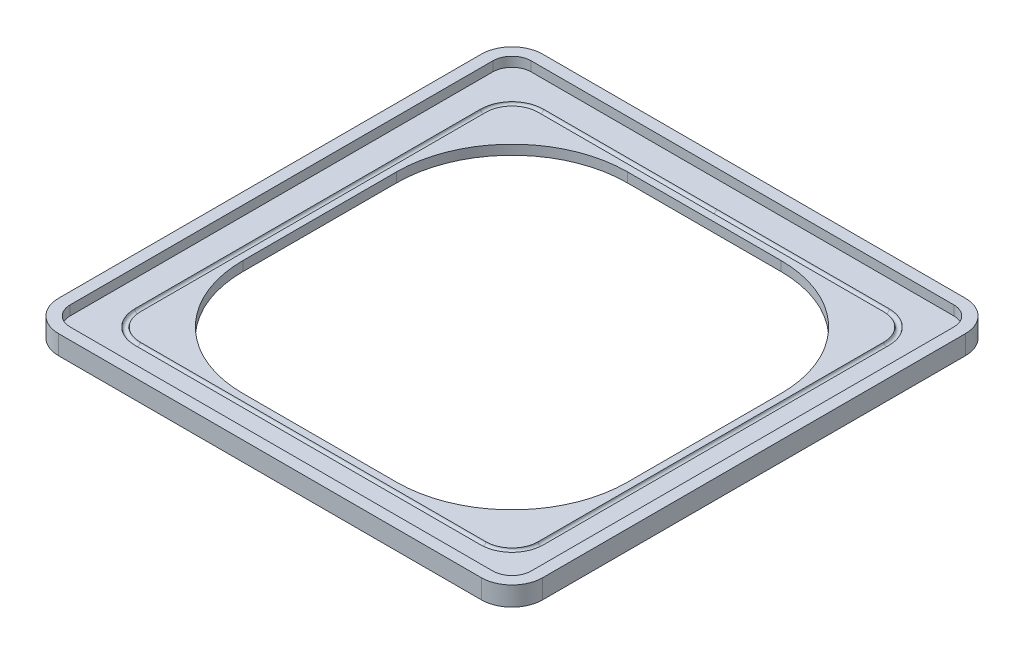
SolidWorks part; units mm, degrees
ref_plane "Front Plane" through (0, 0, 0) normal (0, 0, 1) x (1, 0, 0)
ref_plane "Top Plane" through (0, 0, 0) normal (0, 1, 0) x (1, 0, 0)
ref_plane "Right Plane" through (0, 0, 0) normal (1, 0, 0) x (0, 0, -1)
sketch "Sketch1" plane through (0, 0, 0) normal (0, 1, 0) x (1, 0, 0)
  line L0 (-127, 127) -> (127, 127)
  line L1 (-152.4, -152.4) -> (152.4, -152.4)
  line L2 (-152.4, -152.4) -> (-152.4, 152.4)
  line L3 (-152.4, 152.4) -> (152.4, 152.4)
  line L4 (152.4, -152.4) -> (152.4, 152.4)
  line L5 (-152.4, -152.4) -> (152.4, 152.4) construction
  line L6 (-152.4, 152.4) -> (152.4, -152.4) construction
  line L7 (127, -127) -> (127, 127)
  line L8 (-127, -127) -> (127, -127)
  line L9 (-127, -127) -> (-127, 127)
  line L10 (-146.05, -146.05) -> (-146.05, 146.05) construction
  line L11 (-146.05, 146.05) -> (146.05, 146.05) construction
  line L12 (146.05, -146.05) -> (146.05, 146.05) construction
  line L13 (-146.05, -146.05) -> (146.05, -146.05) construction
  point P0 (0, 0)
  dimension "D1" = 304.8
  dimension "D2" = 304.8
  dimension "D3" = 25.4
  dimension "D4" = 6.35
extrude "Boss-Extrude1" add sketch "Sketch1" along normal blind 6.35
fillet "Fillet1" radius 76.2 4 edges at (127, 3.175, 127) (-127, 3.175, 127) (-127, 3.175, -127) (127, 3.175, -127)
fillet "Fillet2" radius 12.7 4 edges at (-152.4, 3.175, 152.4) (-152.4, 3.175, -152.4) (152.4, 3.175, -152.4) (152.4, 3.175, 152.4)
sketch "Sketch3" plane through (0, 6.35, 0) normal (0, 1, 0) x (1, 0, 0)
  line L1 (114.3, -133.35) -> (-114.3, -133.35)
  line L2 (133.35, -114.3) -> (133.35, 114.3)
  line L3 (114.3, 133.35) -> (-114.3, 133.35)
  line L4 (-133.35, -114.3) -> (-133.35, 114.3)
  arc A0 (133.35, 114.3) -> (114.3, 133.35) centre (114.3, 114.3) ccw
  arc A1 (133.35, -114.3) -> (114.3, -133.35) centre (114.3, -114.3) cw
  arc A2 (-114.3, -133.35) -> (-133.35, -114.3) centre (-114.3, -114.3) cw
  arc A3 (-114.3, 133.35) -> (-133.35, 114.3) centre (-114.3, 114.3) ccw
  point P0 (0, 0)
  dimension "D3" = 19.05
  dimension "D2" = 228.6
  dimension "D1" = 228.6
  dimension "D4" = 133.35
  dimension "D5" = 133.35
sketch "Sketch4" plane through (0, 0, 0) normal (1, 0, 0) x (0, 0, -1)
  circle A0 centre (133.35, 6.35) radius 1.7653
  dimension "D1" = 3.5306
sweep "Cut-Sweep1" cut profiles "Sketch4" path "Sketch3"
sketch "Sketch5" plane through (0, 0, 0) normal (0, -1, 0) x (1, 0, 0)
  line L4 (139.7, 152.4) -> (-139.7, 152.4)
  line L5 (-152.4, 139.7) -> (-152.4, -139.7)
  line L6 (-139.7, -152.4) -> (139.7, -152.4)
  line L7 (152.4, -139.7) -> (152.4, 139.7)
  line L8 (139.7, 160.02) -> (-139.7, 160.02)
  line L9 (160.02, -139.7) -> (160.02, 139.7)
  line L10 (-139.7, -160.02) -> (139.7, -160.02)
  line L11 (-160.02, 139.7) -> (-160.02, -139.7)
  line L12 (139.7, 160.02) -> (-139.7, 160.02)
  line L13 (160.02, -139.7) -> (160.02, 139.7)
  line L14 (-139.7, -160.02) -> (139.7, -160.02)
  line L15 (-160.02, 139.7) -> (-160.02, -139.7)
  arc A4 (-139.7, 152.4) -> (-152.4, 139.7) centre (-139.7, 139.7) ccw
  arc A5 (-152.4, -139.7) -> (-139.7, -152.4) centre (-139.7, -139.7) ccw
  arc A6 (139.7, -152.4) -> (152.4, -139.7) centre (139.7, -139.7) ccw
  arc A7 (152.4, 139.7) -> (139.7, 152.4) centre (139.7, 139.7) ccw
  arc A8 (-139.7, 160.02) -> (-160.02, 139.7) centre (-139.7, 139.7) ccw
  arc A9 (160.02, 139.7) -> (139.7, 160.02) centre (139.7, 139.7) ccw
  arc A10 (139.7, -160.02) -> (160.02, -139.7) centre (139.7, -139.7) ccw
  arc A11 (-160.02, -139.7) -> (-139.7, -160.02) centre (-139.7, -139.7) ccw
  arc A12 (-139.7, 160.02) -> (-160.02, 139.7) centre (-139.7, 139.7) ccw
  arc A13 (160.02, 139.7) -> (139.7, 160.02) centre (139.7, 139.7) ccw
  arc A14 (139.7, -160.02) -> (160.02, -139.7) centre (139.7, -139.7) ccw
  arc A15 (-160.02, -139.7) -> (-139.7, -160.02) centre (-139.7, -139.7) ccw
  dimension "D1" = 7.62
  dimension "D2" = 7.62
extrude "Boss-Extrude2" add sketch "Sketch5" against normal blind 12.7 separate body
